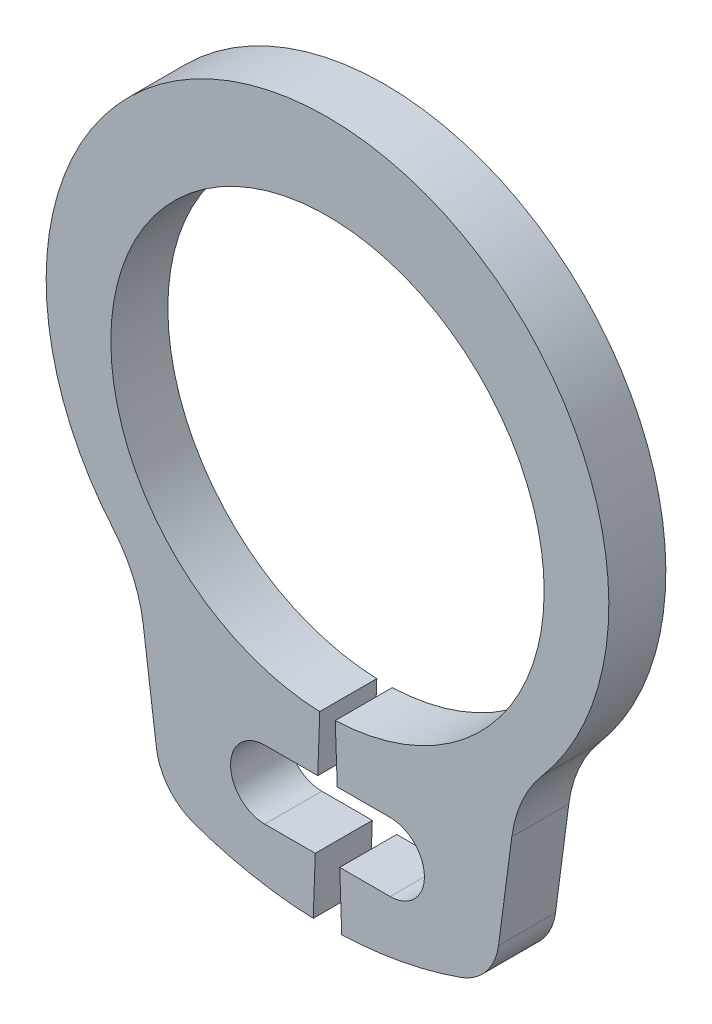
SolidWorks part; units mm, degrees
ref_plane "Plane1" through (0, 0, 0) normal (0, 0, 1) x (1, 0, 0)
ref_plane "Plane2" through (0, 0, 0) normal (0, 1, 0) x (1, 0, 0)
ref_plane "Plane3" through (0, 0, 0) normal (1, 0, 0) x (0, 0, -1)
sketch "Clipboard" plane through (0, 0, 0) normal (0, 0, 1) x (1, 0, 0)
  line L0 (0, 0) -> (1.5, 0)
  line L1 (0, 0) -> (0, 0.9)
  line L2 (0, 0) -> (0, -3.2)
  circle A0 centre (0, 0) radius 0.6
  circle A1 centre (0, 0) radius 4
  dimension "HoleDia" = 1.2
  dimension "ShaftDia" = 8
  dimension "LargeSection" = 1.5
  dimension "SmallSection" = 0.9
  dimension "LugSection" = 3.2
sketch "BodySke" plane through (0, 0, 0) normal (0, 0, 1) x (1, 0, 0)
  line L0 (-1.5431, 0) -> (1.5431, 0) construction
  line L1 (0, 0) -> (0, 5.3) construction
  line L2 (0.1357, -3.7976) -> (0.25, -6.9955)
  line L3 (-0.1357, -3.7976) -> (-0.25, -6.9955)
  line L4 (0, 0) -> (5.5098, -4.3177) construction
  line L5 (0, 0) -> (-5.5098, -4.3177) construction
  line L7 (3.2321, -4.0178) -> (2.9995, -5.7845)
  line L8 (-3.2321, -4.0178) -> (-2.9995, -5.7845)
  circle A0 centre (0, 0) radius 3.8 construction
  arc A1 (0.1357, -3.7976) -> (-0.1357, -3.7976) centre (0, 0) ccw
  arc A2 (3.6994, -2.899) -> (-3.6994, -2.899) centre (0, 0.3659) ccw construction
  arc A3 (0.25, -6.9955) -> (2.3427, -6.5963) centre (0, 0) ccw
  arc A4 (3.7594, -2.8298) -> (3.2321, -4.0178) centre (5.5098, -4.3177) ccw
  arc A5 (-3.2321, -4.0178) -> (-3.7594, -2.8298) centre (-5.5098, -4.3177) ccw
  arc A6 (-2.3427, -6.5963) -> (-0.25, -6.9955) centre (0, 0) ccw
  arc A7 (3.7594, -2.8298) -> (-3.7594, -2.8298) centre (0, 0.3659) ccw
  arc A8 (-3.1693, -4.4951) -> (3.1693, -4.4951) centre (0, 0) ccw construction
  circle A9 centre (1.1, -5.3889) radius 0.6
  circle A10 centre (-1.1, -5.3889) radius 0.6
  arc A11 (2.9995, -5.7845) -> (2.3427, -6.5963) centre (2.0081, -5.654) cw
  arc A12 (-2.9995, -5.7845) -> (-2.3427, -6.5963) centre (-2.0081, -5.654) ccw
  point P28 (2.9237, -6.3602)
  point P31 (-2.9237, -6.3602)
  dimension "HoleDia" = 1.2
  dimension "GrooveDia" = 7.6
  dimension "LugRad" = 7
  dimension "HoleOffsetRad" = 5.5
  dimension "D3" = 1
  dimension "LargeRad" = 5.3
  dimension "SmallRad" = 4.7
  dimension "SmallAngle" = 103.833
  dimension "D2" = 15
  dimension "HoleSpacing" = 2.2
  dimension "Gap" = 0.5
extrude "Body" add sketch "BodySke" against normal blind 1
sketch "NotSke" plane through (0, 0, 0) normal (0, 0, 1) x (1, 0, 0)
  line L0 (1.1, -4.7889) -> (1.1, -5.9889)
  line L1 (1.1, -5.9889) -> (-1.1, -5.9889)
  line L2 (-1.1, -5.9889) -> (-1.1, -4.7889)
  line L3 (-1.1, -4.7889) -> (1.1, -4.7889)
  circle A0 centre (1.1, -5.3889) radius 0.6 construction
  circle A1 centre (-1.1, -5.3889) radius 0.6 construction
extrude "Notch" cut sketch "NotSke" against normal through all
sketch "UnlSke" plane through (0, 0, 0) normal (0, 0, 1) x (1, 0, 0)
  line L0 (2.3427, -2.9919) -> (2.3427, -6.5963)
  line L1 (-2.3427, -2.9919) -> (-2.3427, -6.5963)
  arc A0 (2.3427, -2.9919) -> (-2.3427, -2.9919) centre (0, 0) ccw
  arc A1 (2.3427, -6.5963) -> (-2.3427, -6.5963) centre (0, 0) ccw
  arc A4 (-2.3427, -6.5963) -> (-0.25, -6.9955) centre (0, 0) ccw construction
  arc A5 (0.1357, -3.7976) -> (-0.1357, -3.7976) centre (0, 0) ccw construction
extrude "Unlug" [suppressed] add sketch "UnlSke" against normal through all
equation "' \"ShaftDia@Clipboard\" = 3"
equation "' \"Thickness@Body\" = 0.4"
equation "' \"GrooveDia@BodySke\" = 2.8"
equation "' \"LugSection@Clipboard\" = 1.9"
equation "' \"LargeSection@Clipboard\" = 0.8"
equation "' \"HoleDia@Clipboard\" = 0.8"
equation "' \"ShaftDia@Clipboard\" = 9"
equation "' \"Thickness@Body\" = 1"
equation "' \"GrooveDia@BodySke\" = 8.6"
equation "' \"LugSection@Clipboard\" = 3.3"
equation "' \"LargeSection@Clipboard\" = 1.7"
equation "' \"HoleDia@Clipboard\" = 1.2"
equation "\"SmallSection@Clipboard\" =  \"LargeSection@Clipboard\" * 0.6"
equation "\"Gap@BodySke\" =  \"Thickness@Body\" / 2"
equation "\"LargeRad@BodySke\" =  \"GrooveDia@BodySke\" / 2 +  \"LargeSection@Clipboard\""
equation "\"SmallRad@BodySke\" =  \"GrooveDia@BodySke\" / 2 +  \"SmallSection@Clipboard\""
equation "\"LugRad@BodySke\" = \"GrooveDia@BodySke\" / 2 + \"LugSection@Clipboard\""
equation "\"HoleOffsetRad@BodySke\" = (  \"ShaftDia@Clipboard\" / 2 + \"LugRad@BodySke\" ) / 2"
equation "\"HoleSpacing@BodySke\" = \"Gap@BodySke\"  * 2 +  \"HoleDia@Clipboard\""
equation "\"HoleDia@BodySke\" =  \"HoleDia@Clipboard\""
equation "\"SmallAngle@BodySke\" = atn(\"HoleSpacing@BodySke\" / 2 / sqr(\"HoleOffsetRad@BodySke\"  * \"HoleOffsetRad@BodySke\" - (\"HoleSpacing@BodySke\" / 2) * (\"HoleSpacing@BodySke\" / 2) ))  * 9 * ( 180 / 3.141593)"
